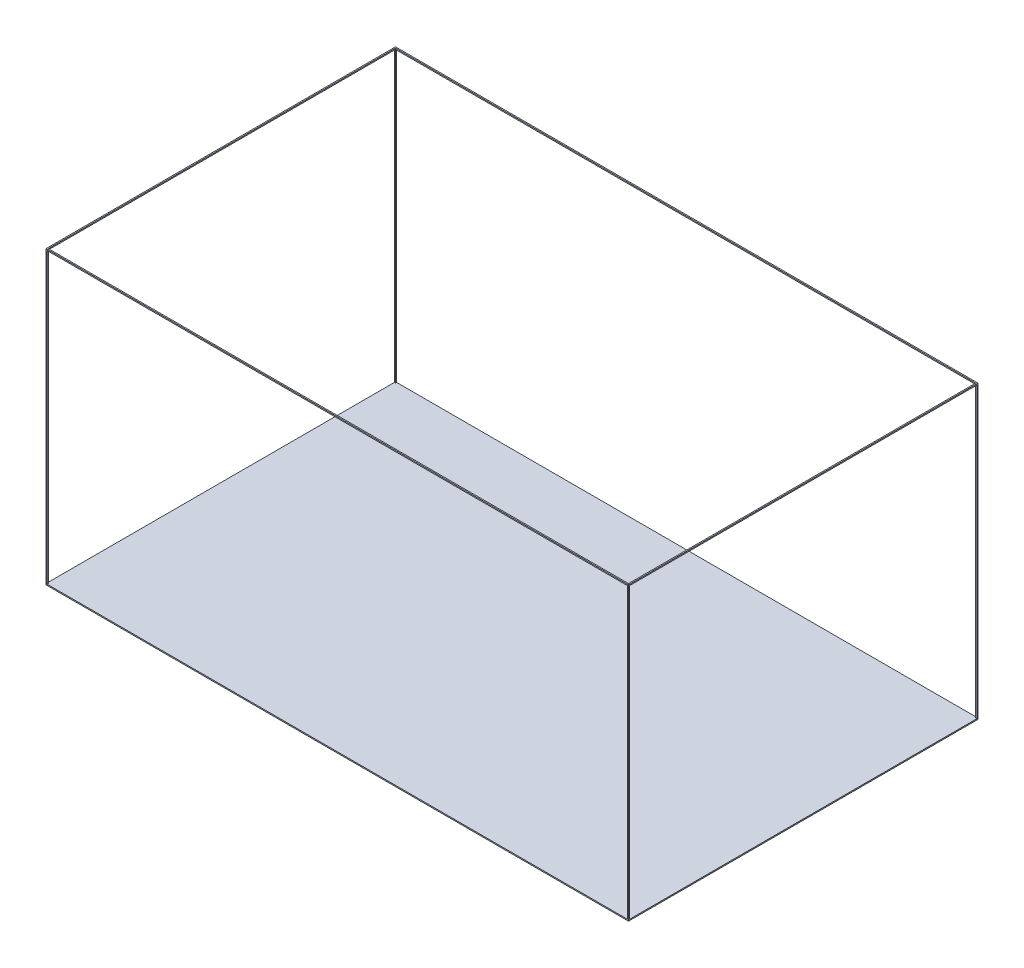
SolidWorks part; units mm, degrees
ref_plane "前视基准面" through (0, 0, 0) normal (0, 0, 1) x (1, 0, 0)
ref_plane "上视基准面" through (0, 0, 0) normal (0, 1, 0) x (1, 0, 0)
ref_plane "右视基准面" through (0, 0, 0) normal (1, 0, 0) x (0, 0, -1)
sketch "草图1" plane through (0, 0, 0) normal (0, 1, 0) x (1, 0, 0)
  line L1 (2500, -1500) -> (-2500, -1500)
  line L2 (2500, -1500) -> (2500, 1500)
  line L3 (2500, 1500) -> (-2500, 1500)
  line L4 (-2500, -1500) -> (-2500, 1500)
  line L5 (2500, -1500) -> (-2500, 1500) construction
  line L6 (2500, 1500) -> (-2500, -1500) construction
  point P0 (0, 0)
  dimension "D1" = 5000
  dimension "D2" = 3000
extrude "凸台-拉伸1" add sketch "草图1" along normal blind 2500
shell "抽壳1" thickness 10
sketch "草图4" plane through (0, 0, 1500) normal (0, 0, 1) x (1, 0, 0)
  line L8 (-2490, 10) -> (2490, 10)
  line L9 (2490, 10) -> (2490, 2490)
  line L10 (2490, 2490) -> (-2490, 2490)
  line L11 (-2490, 2490) -> (-2490, 10)
  line L12 (-2490, 10) -> (2490, 10)
  line L13 (2490, 10) -> (2490, 2490)
  line L14 (2490, 2490) -> (-2490, 2490)
  line L15 (-2490, 2490) -> (-2490, 10)
  dimension "D1" = 10
extrude "切除-拉伸5" cut sketch "草图4" against normal through all
sketch "草图5" plane through (2500, 0, 0) normal (1, 0, 0) x (0, 0, -1)
  line L8 (-1490, 10) -> (1490, 10)
  line L9 (1490, 10) -> (1490, 2490)
  line L10 (1490, 2490) -> (-1490, 2490)
  line L11 (-1490, 2490) -> (-1490, 10)
  line L12 (-1490, 10) -> (1490, 10)
  line L13 (1490, 10) -> (1490, 2490)
  line L14 (1490, 2490) -> (-1490, 2490)
  line L15 (-1490, 2490) -> (-1490, 10)
  dimension "D1" = 10
extrude "切除-拉伸6" cut sketch "草图5" against normal through all
